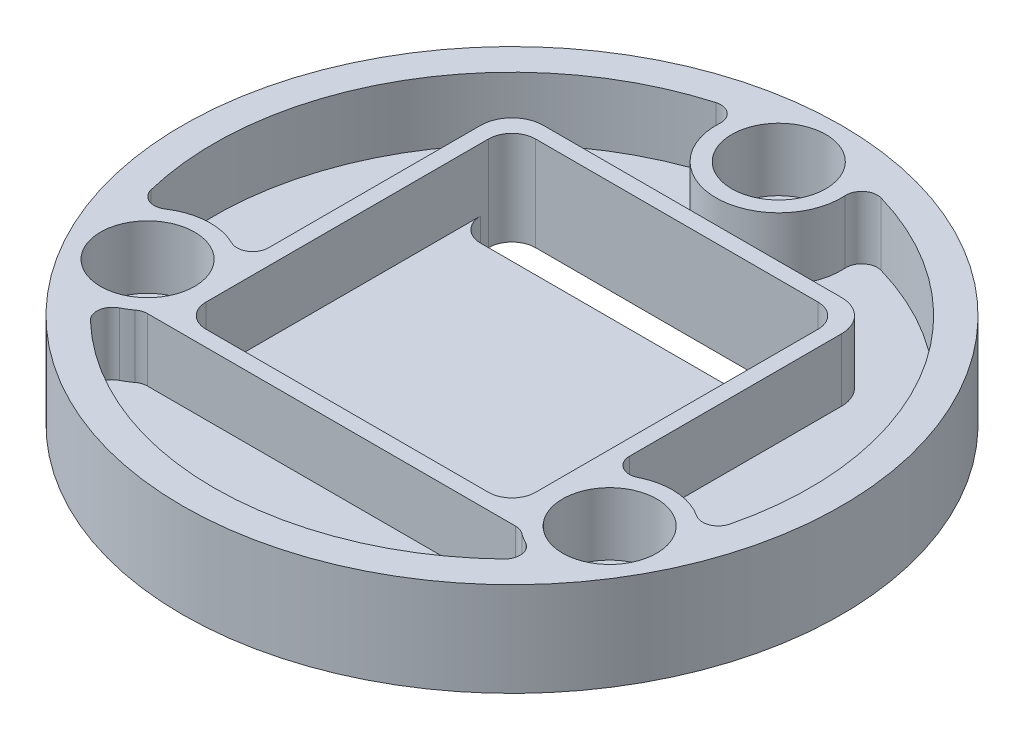
SolidWorks part; units mm, degrees
ref_plane "Front Plane" through (0, 0, 0) normal (0, 0, 1) x (1, 0, 0)
ref_plane "Top Plane" through (0, 0, 0) normal (0, 1, 0) x (1, 0, 0)
ref_plane "Right Plane" through (0, 0, 0) normal (1, 0, 0) x (0, 0, -1)
sketch "Sketch1" plane through (0, 0, 0) normal (0, 1, 0) x (1, 0, 0)
  circle A0 centre (0, 0) radius 21
  dimension "D1" = 42
extrude "Boss-Extrude1" add sketch "Sketch1" along normal blind 2
sketch "Sketch2" plane through (0, 2, 0) normal (0, 1, 0) x (1, 0, 0)
  line L0 (0, 0) -> (0, 21) construction
  line L7 (-14.7224, -8.5) -> (0, 0) construction
  line L8 (14.7224, -8.5) -> (0, 0) construction
  line L9 (-11.5, -4.0211) -> (-11.5, 9.5)
  line L10 (9, -10.5) -> (-9, -10.5)
  line L11 (10.5, -9) -> (10.5, 9)
  line L12 (9, 10.5) -> (-9, 10.5)
  line L13 (-10.5, -9) -> (-10.5, 9)
  line L14 (10.5, -10.5) -> (-10.5, 10.5) construction
  line L15 (10.5, 10.5) -> (-10.5, -10.5) construction
  line L16 (11.5, -11.5) -> (-11.5, -11.5)
  line L18 (9.5, 11.5) -> (-9.5, 11.5)
  line L20 (11.5, -11.5) -> (-11.5, 11.5) construction
  line L21 (11.5, 11.5) -> (-11.5, -11.5) construction
  line L22 (11.5, -4.0211) -> (11.5, 9.5)
  line L23 (11.5, -11.5) -> (11.7224, -11.5)
  line L24 (-11.5, -11.5) -> (-11.7224, -11.5)
  circle A0 centre (0, 0) radius 21
  circle A1 centre (0, 0) radius 21 construction
  arc A2 (-5.2686, 18.2549) -> (-18.4435, -4.5647) centre (0, 0) ccw
  circle A3 centre (0, 0) radius 21
  arc A4 (-5.2686, 18.2549) -> (-18.4435, -4.5647) centre (0, 0) ccw
  circle A5 centre (0, 17) radius 3
  circle A6 centre (14.7224, -8.5) radius 3
  circle A7 centre (-14.7224, -8.5) radius 3
  circle A8 centre (0, 0) radius 17 construction
  arc A9 (18.4435, -4.5647) -> (5.2686, 18.2549) centre (0, 0) ccw
  arc A10 (-13.1749, -13.6902) -> (13.1749, -13.6902) centre (0, 0) ccw
  arc A11 (-3.9931, 17.2353) -> (0, 13) centre (0, 17) ccw
  arc A12 (16.9227, -5.1595) -> (12.9445, -4.9169) centre (14.7224, -8.5) ccw
  arc A13 (-12.9297, -12.0758) -> (-12.3224, -11.7) centre (-14.7224, -8.5) ccw
  arc A16 (0, 13) -> (3.9931, 17.2353) centre (0, 17) ccw
  arc A17 (12.3224, -11.7) -> (12.9297, -12.0758) centre (14.7224, -8.5) ccw
  arc A18 (-12.9445, -4.9169) -> (-16.9227, -5.1595) centre (-14.7224, -8.5) ccw
  arc A33 (16.9227, -5.1595) -> (18.4435, -4.5647) centre (17.4728, -4.3244) ccw
  arc A34 (12.9297, -12.0758) -> (13.1749, -13.6902) centre (12.4815, -12.9697) cw
  arc A35 (-12.9297, -12.0758) -> (-13.1749, -13.6902) centre (-12.4815, -12.9697) ccw
  arc A36 (-16.9227, -5.1595) -> (-18.4435, -4.5647) centre (-17.4728, -4.3244) cw
  arc A37 (5.2686, 18.2549) -> (3.9931, 17.2353) centre (4.9913, 17.2941) ccw
  arc A38 (-5.2686, 18.2549) -> (-3.9931, 17.2353) centre (-4.9913, 17.2941) cw
  arc A39 (11.7224, -11.5) -> (12.3224, -11.7) centre (11.7224, -12.5) cw
  arc A40 (-11.5, -4.0211) -> (-12.9445, -4.9169) centre (-12.5, -4.0211) cw
  arc A41 (11.5, -4.0211) -> (12.9445, -4.9169) centre (12.5, -4.0211) ccw
  arc A42 (-11.7224, -11.5) -> (-12.3224, -11.7) centre (-11.7224, -12.5) ccw
  arc A43 (18.4435, -4.5647) -> (5.2686, 18.2549) centre (0, 0) ccw
  arc A44 (-13.1749, -13.6902) -> (13.1749, -13.6902) centre (0, 0) ccw
  arc A45 (-9, 10.5) -> (-10.5, 9) centre (-9, 9) ccw
  arc A46 (10.5, 9) -> (9, 10.5) centre (9, 9) ccw
  arc A47 (9, -10.5) -> (10.5, -9) centre (9, -9) ccw
  arc A48 (-9, -10.5) -> (-10.5, -9) centre (-9, -9) cw
  arc A49 (-9.5, 11.5) -> (-11.5, 9.5) centre (-9.5, 9.5) ccw
  arc A50 (11.5, 9.5) -> (9.5, 11.5) centre (9.5, 9.5) ccw
  circle M16 centre (0, 0) radius 21
  dimension "D1" = 38
  dimension "D2" = 21
  dimension "D3" = 42
  dimension "D4" = 4
  dimension "D6" = 120
  dimension "D7" = 6
  dimension "D9" = 21
  dimension "D10" = 1
  dimension "D11" = 1
  dimension "D12" = 1
  dimension "D13" = 1
  dimension "D16" = 1.5
  dimension "D17" = 2
  dimension "D5" = 17
  dimension "D8" = 120
  dimension "D14" = 23
  dimension "D15" = 23
extrude "Boss-Extrude2" add sketch "Sketch2" along normal blind 4 contours A42 L24 L16 L23 A39 A17 A34 A10 A35 A13 A41 L22 L18 L9 A40 A18 A36 A2 A38 A11 A16 A37 A9 A33 A12 A7 A6 A5 L10 L13 L12 L11 M16
sketch "Sketch3" plane through (0, 2, 0) normal (0, 1, 0) x (1, 0, 0)
  line L0 (0, 0) -> (0, 10.5) construction
  line L1 (9, 10.5) -> (-9, 10.5) construction
  line L2 (9, 10.5) -> (-9, 10.5) construction
  line L3 (9, 7) -> (-9, 7)
  line L4 (10.5, 8.5) -> (10.5, 9)
  line L5 (9, 10.5) -> (-9, 10.5)
  line L6 (-10.5, 8.5) -> (-10.5, 9)
  line L7 (10.5, 7) -> (-10.5, 10.5) construction
  line L8 (10.5, 10.5) -> (-10.5, 7) construction
  line L9 (-10.5, -9) -> (-10.5, 9) construction
  arc A0 (-9, 10.5) -> (-10.5, 9) centre (-9, 9) ccw
  arc A1 (10.5, 9) -> (9, 10.5) centre (9, 9) ccw
  arc A2 (9, 7) -> (10.5, 8.5) centre (9, 8.5) ccw
  arc A3 (-9, 7) -> (-10.5, 8.5) centre (-9, 8.5) cw
  circle A4 centre (0, 17) radius 2
  circle A5 centre (14.7224, -8.5) radius 2
  circle A6 centre (-14.7224, -8.5) radius 2
  point P5 (0, 8.75)
  dimension "D3" = 1.5
  dimension "D1" = 4
  dimension "D2" = 3.5
extrude "Cut-Extrude1" cut sketch "Sketch3" against normal blind 2
sketch "Sketch4" plane through (0, 0, 0) normal (0, 0, 1) x (1, 0, 0)
  line L0 (21, 6) -> (-21, 6) construction
  point P0 (0, 6)
  point P1 (0, 0)
  dimension "D1" = 6
